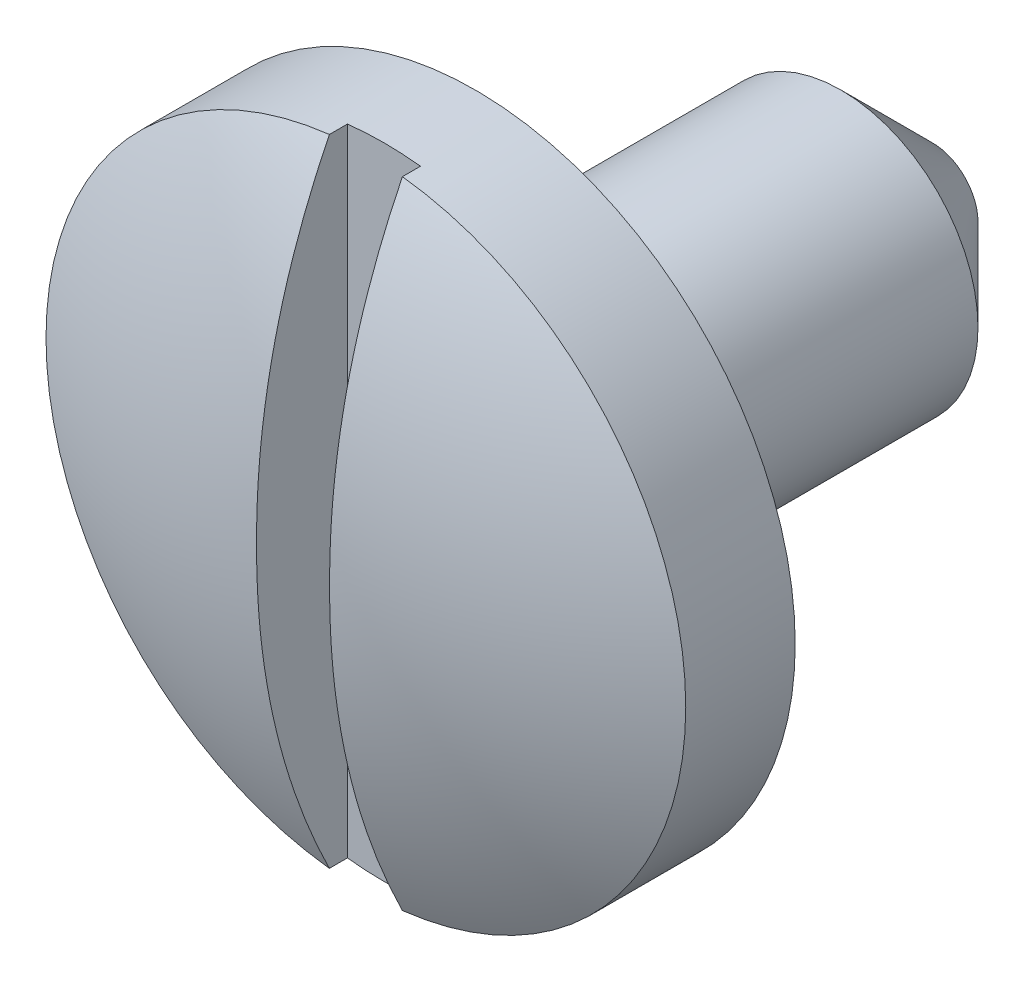
SolidWorks part; units mm, degrees
material "1.4006 (X10Cr13)"
ref_plane "Спереди" through (0, 0, 0) normal (0, 0, 1) x (1, 0, 0)
ref_plane "Сверху" through (0, 0, 0) normal (0, 1, 0) x (1, 0, 0)
ref_plane "Справа" through (0, 0, 0) normal (1, 0, 0) x (0, 0, -1)
sketch "Эскиз1" plane through (0, 0, 0) normal (0, 0, 1) x (1, 0, 0)
  circle A0 centre (0, 0) radius 3.5
extrude "Бобышка-Вытянуть1" add sketch "Эскиз1" along normal blind 2
sketch "Эскиз2" plane through (0, 0, 2) normal (0, 0, 1) x (1, 0, 0)
  line L1 (-0.3997, -3.7275) -> (0.3997, -3.7275)
  line L2 (-0.3997, -3.7275) -> (-0.3997, 3.7275)
  line L3 (-0.3997, 3.7275) -> (0.3997, 3.7275)
  line L4 (0.3997, -3.7275) -> (0.3997, 3.7275)
  line L5 (-0.3997, -3.7275) -> (0.3997, 3.7275) construction
  line L6 (-0.3997, 3.7275) -> (0.3997, -3.7275) construction
  point P0 (0, 0)
extrude "Вырез-Вытянуть1" cut sketch "Эскиз2" against normal blind 1
sketch "Эскиз3" plane through (0, 0, 0) normal (0, 0, -1) x (-1, 0, 0)
  circle A0 centre (0, 0) radius 1.5
extrude "Бобышка-Вытянуть2" add sketch "Эскиз3" along normal blind 5
chamfer "Фаска1" distance 1 angle 45 1 edges at (-1.5, 0, -5)
ref_plane "Плоскость2" through (0, 0, 0) normal (0, 1, 0) x (1, 0, 0)
sketch "Эскиз6" plane through (0, 0, 0) normal (0, 1, 0) x (1, 0, 0)
  line L0 (0.1, -2) -> (3.5036, -2)
  line L1 (3.5036, -2) -> (3.5036, -1.1958)
  line L2 (0, -4.4414) -> (0, 1.3263) construction
  arc A0 (0.1, -2) -> (3.5036, -1.1958) centre (0.1, 5.6047) ccw
  point P8 (0, 0)
  point P9 (0, 0)
  point P12 (0, 0)
  point P13 (0, 0)
  point P14 (0, 0)
  point P15 (0, 0)
revolve "Вырез-Повернуть3" cut sketch "Эскиз6" angle 360 about L2
